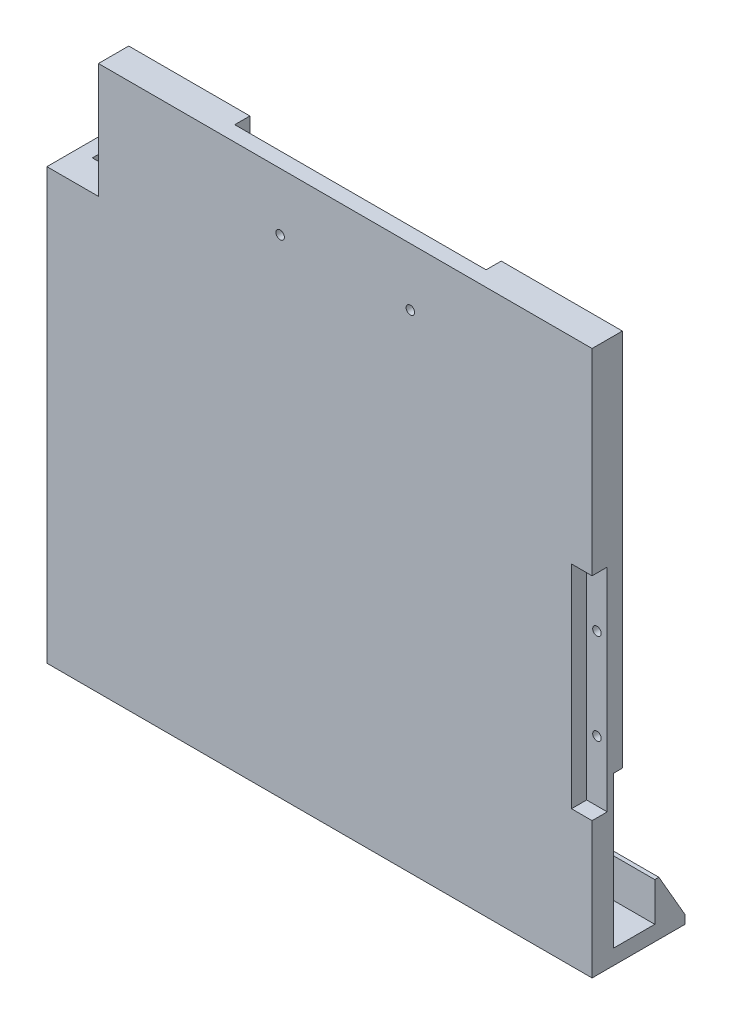
SolidWorks part; units mm, degrees
ref_plane "Alzado" through (0, 0, 0) normal (0, 0, 1) x (1, 0, 0)
ref_plane "Planta" through (0, 0, 0) normal (0, 1, 0) x (1, 0, 0)
ref_plane "Vista lateral" through (0, 0, 0) normal (1, 0, 0) x (0, 0, -1)
sketch "Croquis1" plane through (0, 0, 0) normal (0, 0, 1) x (1, 0, 0)
  line L1 (0, 0) -> (180, 0)
  line L2 (0, 0) -> (0, 180)
  line L3 (0, 180) -> (180, 180)
  line L4 (180, 0) -> (180, 180)
  dimension "D1" = 180
extrude "Saliente-Extruir1" add sketch "Croquis1" along normal blind 30.7
sketch "Croquis2" plane through (0, 0, 0) normal (0, 0, -1) x (-1, 0, 0)
  line L0 (-180, 0) -> (-180, 180) construction
  line L1 (-180, 17.79) -> (-17.01, 17.79)
  line L2 (-180, 17.79) -> (-180, 180)
  line L3 (-180, 180) -> (-17.01, 180)
  line L4 (-17.01, 17.79) -> (-17.01, 180)
  line L5 (-180, 180) -> (0, 180) construction
  line L6 (0, 180) -> (0, 0) construction
  line L7 (0, 0) -> (-180, 0) construction
  dimension "D1" = 17.01
  dimension "D2" = 17.79
extrude "Cortar-Extruir1" cut sketch "Croquis2" against normal blind 20.7
sketch "Croquis4" plane through (0, 180, 0) normal (0, 1, 0) x (1, 0, 0)
  line L0 (17.01, -20.7) -> (17.01, 0) construction
  line L1 (180, -20.7) -> (5, -20.7)
  line L2 (180, -20.7) -> (180, -10)
  line L3 (180, -10) -> (5, -10)
  line L4 (5, -20.7) -> (5, -10)
  dimension "D1" = 10.7
  dimension "D2" = 12.01
extrude "Cortar-Extruir2" cut sketch "Croquis4" against normal offset from surface (175 mm away) 5 up to face at (90, 0, 15.35)
sketch "Croquis5" plane through (0, 0, 0) normal (-1, 0, 0) x (0, 0, 1)
  line L0 (30.7, 180) -> (30.7, 0) construction
  line L1 (0, 180) -> (30.7, 180)
  line L2 (0, 180) -> (0, 142)
  line L3 (0, 142) -> (30.7, 142)
  line L4 (30.7, 180) -> (30.7, 142)
  dimension "D1" = 38
extrude "Cortar-Extruir3" cut sketch "Croquis5" against normal up to surface (17.01 mm away) up to face at (17.01, 98.895, 5)
sketch "Croquis6" plane through (0, 0, 20.7) normal (0, 0, -1) x (-1, 0, 0)
  line L1 (-140, 180) -> (-57.01, 180)
  line L2 (-140, 180) -> (-140, 142)
  line L3 (-140, 142) -> (-57.01, 142)
  line L4 (-57.01, 180) -> (-57.01, 142)
  line L10 (-17.01, 180) -> (-17.01, 142) construction
  line L11 (-180, 180) -> (-180, 5) construction
  line L12 (-17.01, 180) -> (-180, 180) construction
  dimension "D1" = 38
  dimension "D2" = 40
  dimension "D3" = 40
extrude "Cortar-Extruir4" cut sketch "Croquis6" against normal blind 5
sketch "Croquis7" plane through (0, 0, 30.7) normal (0, 0, 1) x (1, 0, 0)
  line L0 (180, 0) -> (180, 180) construction
  line L1 (173.2, 115) -> (180, 115)
  line L2 (173.2, 115) -> (173.2, 45)
  line L3 (173.2, 45) -> (180, 45)
  line L4 (180, 115) -> (180, 45)
  line L5 (173.2, 45) -> (180, 45) construction
extrude "Cortar-Extruir5" cut sketch "Croquis7" against normal blind 5
sketch "Croquis8" plane through (0, 0, 20.7) normal (0, 0, -1) x (-1, 0, 0)
  line L0 (-180, 180) -> (-180, 5) construction
  line L1 (-5, 5) -> (-180, 5)
  line L2 (-5, 5) -> (-5, 55)
  line L3 (-5, 55) -> (-180, 55)
  line L4 (-180, 5) -> (-180, 55)
  dimension "D1" = 50
extrude "Cortar-Extruir6" cut sketch "Croquis8" against normal blind 3
chamfer "Chaflán1" distance 15 angle 30 2 edges at (17.01, 79.895, 0) (98.505, 17.79, 0)
sketch "Croquis9" plane through (0, 0, 30.7) normal (0, 0, 1) x (1, 0, 0)
  line L0 (57.01, 142) -> (57.01, 180) construction
  line L1 (140, 180) -> (140, 142) construction
  circle A0 centre (176.6, 65) radius 1.4
  circle A1 centre (176.6, 95) radius 1.4
  circle A2 centre (120, 161) radius 1.4
  circle A3 centre (77.01, 161) radius 1.4
  point P14 (0, 0)
  point P15 (140, 161)
  dimension "D1" = 2.8
  dimension "D2" = 20
  dimension "D3" = 20
extrude "Cortar-Extruir7" cut sketch "Croquis9" against normal blind 20
